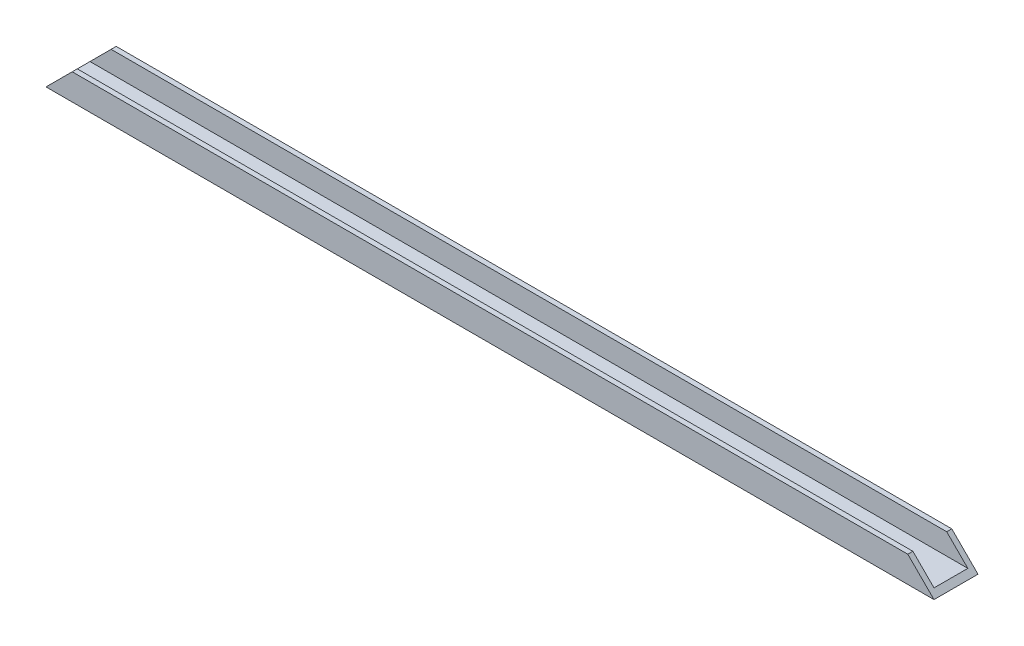
SolidWorks part; units mm, degrees
ref_plane "Front Plane" through (0, 0, 0) normal (0, 0, 1) x (1, 0, 0)
ref_plane "Top Plane" through (0, 0, 0) normal (0, 1, 0) x (1, 0, 0)
ref_plane "Right Plane" through (0, 0, 0) normal (1, 0, 0) x (0, 0, -1)
sketch "Sketch1" plane through (0, 0, 0) normal (1, 0, 0) x (0, 0, -1)
  line L0 (-4, 5) -> (-4, 0)
  line L1 (-4, 0) -> (4, 0)
  line L2 (4, 0) -> (4, 5)
  line L3 (-5.2, 5) -> (-5.2, -1.2)
  line L4 (-5.2, -1.2) -> (5.2, -1.2)
  line L5 (5.2, -1.2) -> (5.2, 5)
  line L6 (-5.2, 5) -> (-4, 5)
  line L7 (4, 5) -> (5.2, 5)
  point P2 (0, 0)
  dimension "D1" = 5
  dimension "D2" = 5
  dimension "D3" = 8
  dimension "D4" = 1.2
  dimension "D5" = 1.2
  dimension "D6" = 1.2
extrude "Boss-Extrude1" add sketch "Sketch1" along normal mid plane 210
sketch "Sketch3" plane through (0, 0, 5.2) normal (0, 0, 1) x (1, 0, 0)
  line L0 (-105, 5) -> (-105, -1.2)
  line L1 (-105, -1.2) -> (-98.8, 5)
  line L2 (105, 5) -> (-105, 5) construction
  line L3 (-98.8, 5) -> (-105, 5)
  line L4 (0, 32.8147) -> (0, -57.253) construction
  line L5 (105, 5) -> (105, -1.2)
  line L6 (98.8, 5) -> (105, 5)
  line L7 (105, -1.2) -> (98.8, 5)
  dimension "D1" = 45
extrude "Cut-Extrude1" cut sketch "Sketch3" against normal through all
